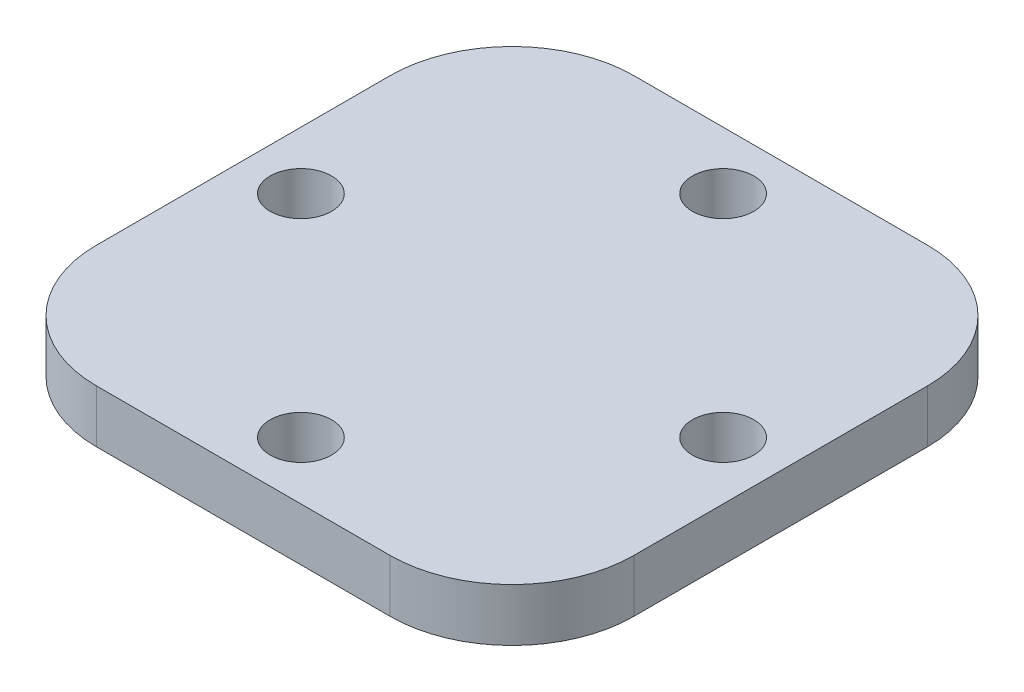
SolidWorks part; units mm, degrees
ref_plane "Front Plane" through (0, 0, 0) normal (0, 0, 1) x (1, 0, 0)
ref_plane "Top Plane" through (0, 0, 0) normal (0, 1, 0) x (1, 0, 0)
ref_plane "Right Plane" through (0, 0, 0) normal (1, 0, 0) x (0, 0, -1)
sketch "Sketch1" plane through (0, 0, 0) normal (0, 1, 0) x (1, 0, 0)
  line L1 (-7.65, -14) -> (7.65, -14)
  line L2 (-14, -7.65) -> (-14, 7.65)
  line L3 (-7.65, 14) -> (7.65, 14)
  line L4 (14, -7.65) -> (14, 7.65)
  line L5 (-14, -14) -> (14, 14) construction
  line L6 (-14, 14) -> (14, -14) construction
  arc A0 (7.65, 14) -> (14, 7.65) centre (7.65, 7.65) cw
  arc A1 (-7.65, -14) -> (-14, -7.65) centre (-7.65, -7.65) cw
  arc A2 (14, -7.65) -> (7.65, -14) centre (7.65, -7.65) cw
  arc A3 (-14, 7.65) -> (-7.65, 14) centre (-7.65, 7.65) cw
  circle A5 centre (-11, 0) radius 1.6
  circle A7 centre (0, -11) radius 1.6
  circle A9 centre (11, 0) radius 1.6
  circle A11 centre (0, 11) radius 1.6
  point P0 (0, 0)
  dimension "D1" = 6.35
  dimension "D2" = 28
  dimension "D3" = 28
extrude "Boss-Extrude1" add sketch "Sketch1" along normal blind 2.75
